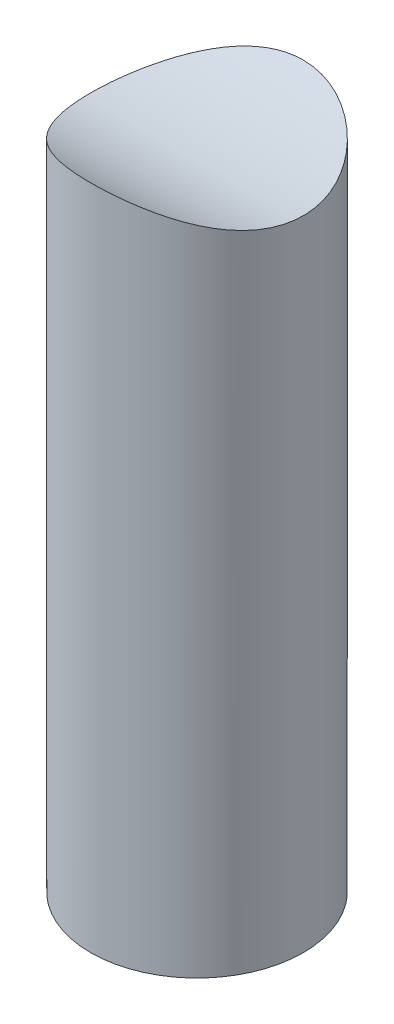
SolidWorks part; units mm, degrees
ref_plane "Front" through (0, 0, 0) normal (0, 0, 1) x (1, 0, 0)
ref_plane "Top" through (0, 0, 0) normal (0, 1, 0) x (1, 0, 0)
ref_plane "Right" through (0, 0, 0) normal (1, 0, 0) x (0, 0, -1)
sketch "Croquis1" plane through (0, 0, 0) normal (0, 1, 0) x (1, 0, 0)
  circle A0 centre (0, 0) radius 25
  dimension "D1" = 50
extrude "Saliente-Extruir1" add sketch "Croquis1" along normal blind 170
sketch "Croquis5" plane through (0, 0, 0) normal (1, 0, 0) x (0, 0, -1)
  line L0 (0, 27.5) -> (0, -27.5) construction
  line L1 (25, 170) -> (-25, 170) construction
  circle A0 centre (0, 200) radius 50
  dimension "D2" = 100
  dimension "D1" = 30
extrude "Cortar-Extruir1" cut sketch "Croquis5" against normal through all both and the other way through all
